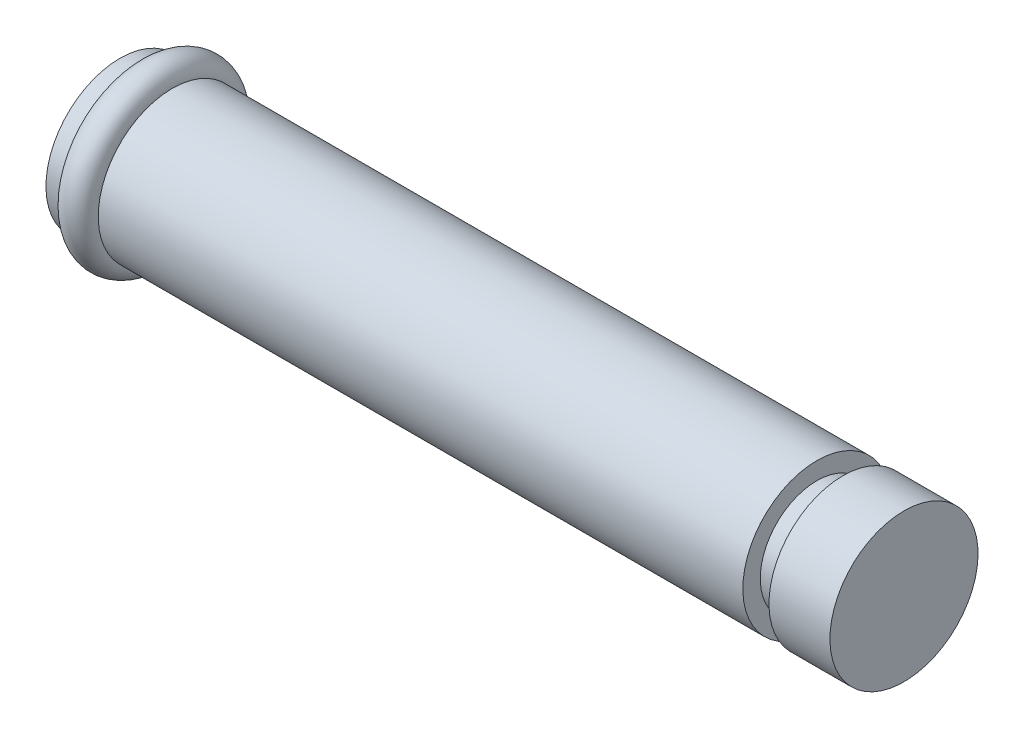
SolidWorks part; units mm, degrees
ref_plane "Front Plane" through (0, 0, 0) normal (0, 0, 1) x (1, 0, 0)
ref_plane "Top Plane" through (0, 0, 0) normal (0, 1, 0) x (1, 0, 0)
ref_plane "Right Plane" through (0, 0, 0) normal (1, 0, 0) x (0, 0, -1)
sketch "Sketch1" plane through (0, 0, 0) normal (0, 0, 1) x (1, 0, 0)
  line L0 (-44, 4.25) -> (-45, 4.25)
  line L1 (0, 0) -> (-45, 0)
  line L2 (0, 0) -> (0, 4.25)
  line L3 (0, 4.25) -> (-3.5, 4.25)
  line L4 (-45, 0) -> (-45, 4.25)
  line L6 (-44, 4.25) -> (-44, 3.25)
  line L7 (-44, 3.25) -> (-42, 3.25)
  line L8 (-42, 4.25) -> (-42, 3.25)
  line L10 (-5, 4.25) -> (-5, 3.25)
  line L11 (-5, 3.25) -> (-3.5, 3.25)
  line L12 (-3.5, 4.25) -> (-3.5, 3.25)
  line L13 (-5, 4.25) -> (-42, 4.25)
  point P13 (-2.9957, 2.4824)
  dimension "D1" = 4.25
  dimension "D2" = 45
  dimension "D3" = 1
  dimension "D4" = 1
  dimension "D5" = 3.5
  dimension "D6" = 2
  dimension "D7" = 1.5
revolve "Revolve1" add sketch "Sketch1" angle 360 about L1
sketch "Sketch2" plane through (0, 0, 0) normal (0, 0, 1) x (1, 0, 0)
  line L0 (-44, -4.25) -> (-44, 4.25) construction
  line L1 (-42, 3.25) -> (-44, 3.25) construction
  circle A0 centre (-43.05, 4.2) radius 0.925
  dimension "D3" = 1.85
  dimension "D1" = 0.95
  dimension "D2" = 0.95
revolve "Revolve2" add sketch "Sketch2" angle 360 about axis through (0, 0, 0) along (1, 0, 0)
